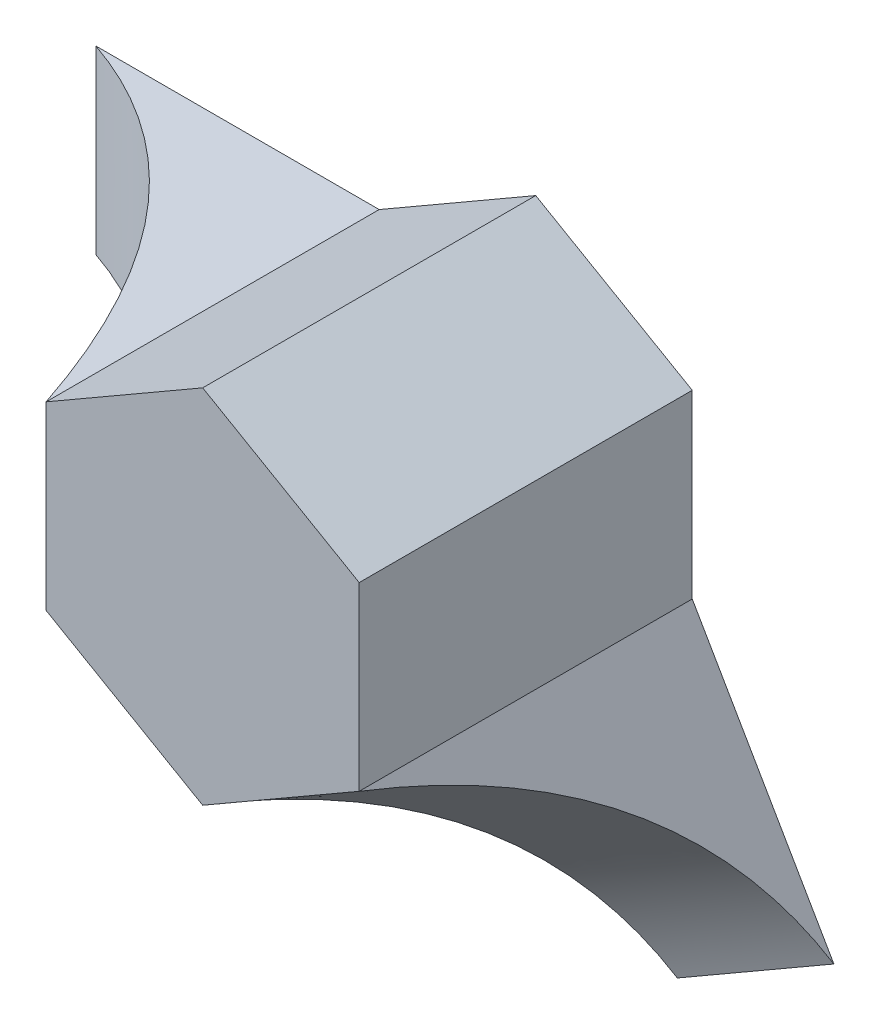
SolidWorks part; units mm, degrees
ref_plane "Alzado" through (0, 0, 0) normal (0, 0, 1) x (1, 0, 0)
ref_plane "Planta" through (0, 0, 0) normal (0, 1, 0) x (1, 0, 0)
ref_plane "Vista lateral" through (0, 0, 0) normal (1, 0, 0) x (0, 0, -1)
sketch "Croquis1" plane through (0, 0, 0) normal (0, 0, 1) x (1, 0, 0)
  line L0 (0, -55) -> (0, 55) construction
  line L1 (44.6491, 25.7781) -> (0, 51.5563)
  line L2 (0, 51.5563) -> (-44.6491, 25.7781)
  line L3 (-44.6491, 25.7781) -> (-44.6491, -25.7781)
  line L4 (-44.6491, -25.7781) -> (0, -51.5563)
  line L5 (0, -51.5563) -> (44.6491, -25.7781)
  line L6 (44.6491, -25.7781) -> (44.6491, 25.7781)
  circle A0 centre (0, 0) radius 44.6491 construction
extrude "Saliente-Extruir1" add sketch "Croquis1" along normal mid plane 95
ref_plane "Plano1" through (0, 0, -47.5) normal (0, 0, -1) x (-1, 0, 0)
ref_plane "Plano2" through (22.3245, 12.8891, 0) normal (-0.866, -0.5, 0) x (0, 0, -1)
sketch "Croquis6" plane through (22.3245, 12.8891, 0) normal (-0.866, -0.5, 0) x (0, 0, -1)
  line L0 (-47.517, 44.6491) -> (47.5, 44.6491)
  line L1 (47.5, 44.6491) -> (47.5, 125.4506)
  parabola Q0 (47.5, 125.4506) -> (-47.517, 44.6491) focus (-5.0493, 134.6491) apex (40.9493, 110.2965)
extrude "Saliente-Extruir2" add sketch "Croquis6" along normal up to vertex (51.5563 mm away) up to point (0, -51.5563, 47.5)
ref_plane "Plano3" through (0, 25.7781, 0) normal (0, 1, 0) x (0, 0, -1)
sketch "Croquis8" plane through (0, 25.7781, 0) normal (0, 1, 0) x (0, 0, -1)
  line L0 (-47.5, -44.6491) -> (-47.3672, -44.6241)
  line L1 (47.5, 44.6491) -> (47.5, 125.4529)
  line L4 (-47.4908, 44.6691) -> (-47.5, 44.6491)
  line L6 (-47.5, 44.6491) -> (47.5, 44.6491)
  parabola Q0 (47.5, 125.4529) -> (-47.4908, 44.6691) focus (-5.0473, 134.651) apex (40.9469, 110.2958)
  parabola Q2 (-47.3672, -44.6241) -> (-47.517, -44.6491) focus (36.2269, 11.2772) apex (52.6885, 6.9196)
extrude "Saliente-Extruir3" add sketch "Croquis8" against normal up to vertex (51.5563 mm away) contours L1 Q0 L4 L6 up to point (-44.6491, -25.7781, 47.5)
